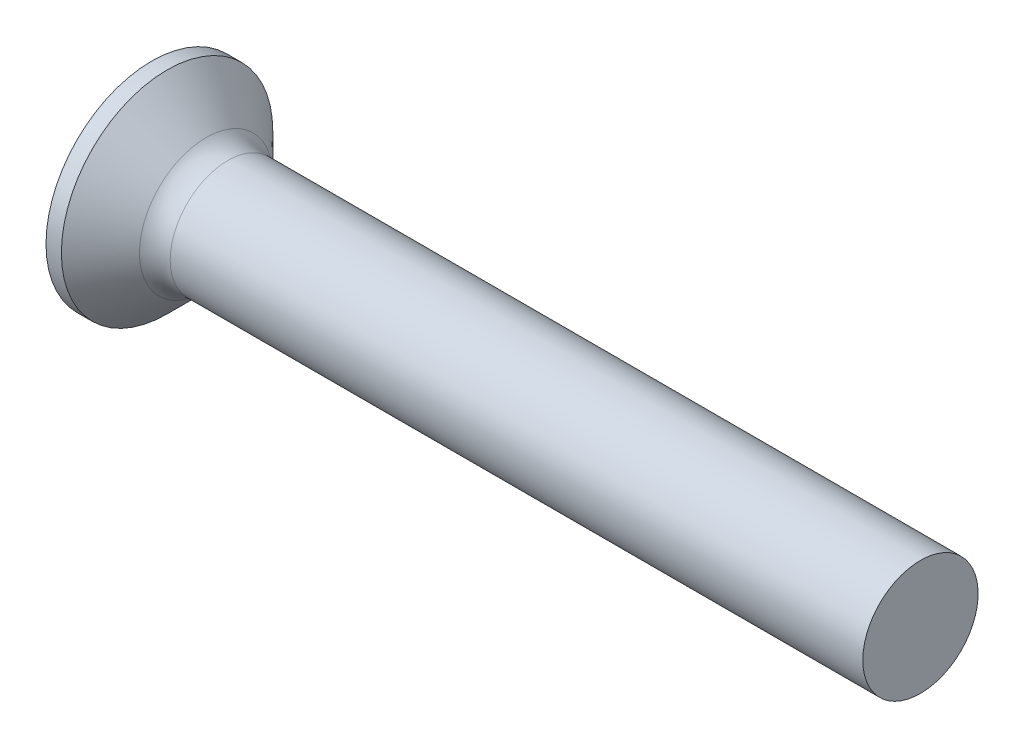
SolidWorks part; units mm, degrees
revolve "Base-Revolve" add sketch "BodySke"
sketch "BodySke" plane through (0, 0, 0) normal (0, 0, 1) x (1, 0, 0)
  line L0 (0, 0) -> (0, 2.75)
  line L1 (0, 2.75) -> (0.4, 2.75)
  line L2 (1.65, 1.5) -> (20, 1.5)
  line L3 (20, 1.5) -> (20, 0)
  line L4 (20, 0) -> (0, 0)
  line L5 (-6.35, 0) -> (82.55, 0) construction
  line L6 (1.65, -1.5) -> (20, -1.5) construction
  line L7 (0.4, -2.75) -> (1.65, -1.5) construction
  line L8 (0.4, 2.75) -> (1.65, 1.5)
  line L9 (0, -2.75) -> (0.4, -2.75) construction
  line L10 (2.15, 3.0875) -> (2.15, -6.4375) construction
  line L11 (0, 6.35) -> (0, -3.175) construction
  dimension "Diameter" = 3
  dimension "Length" = 20
  dimension "Head_ht" = 1.65
  dimension "Head_dia" = 5.5
  dimension "Head_ang" = 90
  dimension "D6" = 0.4
  dimension "Advance" = 0.5
  dimension "Thread_nom" = 20
cosmetic thread "ThreadCosmetic"
fillet "Fillet1" radius 0.8 1 edges at (1.65, 0, 1.5)
ref_plane "Plane1" through (0, 0, 0) normal (0, 0, 1) x (1, 0, 0)
ref_plane "Plane2" through (0, 0, 0) normal (0, 1, 0) x (1, 0, 0)
ref_plane "Plane3" through (0, 0, 0) normal (1, 0, 0) x (0, 0, -1)
sketch "Sketch3" plane through (0, 0, 0) normal (-1, 0, 0) x (0, 0, 1)
  line L0 (-0.37, 1.5) -> (0.37, 1.5)
  line L1 (0.37, 1.5) -> (0.37, -1.5)
  line L2 (0.37, -1.5) -> (-0.37, -1.5)
  line L3 (-0.37, -1.5) -> (-0.37, 1.5)
  dimension "Cross_dia" = 3
  dimension "Cross_width" = 0.74
  dimension "D1" = 1.5
  dimension "D2" = 0.37
ref_plane "Plane4" through (2.01, 0, 0) normal (-1, 0, 0) x (0, 0, 1)
sketch "Sketch4" plane through (2.01, 0, 0) normal (-1, 0, 0) x (0, 0, 1)
  line L0 (-0.37, 0.4979) -> (0.37, 0.4979)
  line L3 (0.37, 0.4979) -> (0.37, -0.4979)
  line L4 (0.37, -0.4979) -> (-0.37, -0.4979)
  line L5 (-0.37, -0.4979) -> (-0.37, 0.4979)
  dimension "D2" = 0.9957
  dimension "D1" = 0.74
  dimension "D4" = 0.4979
  dimension "D3" = 0.37
loft "Recess" cut profiles "Sketch3", "Sketch4"
pattern_circular "RecPat" count 2 every 90 about axis through (0, 0, 0) along (1, 0, 0) of "Recess"
sketch "RecCorSke" plane through (0, 0, 0) normal (0, 0, 1) x (1, 0, 0)
  line L0 (-3.175, 0) -> (15.875, 0) construction
  line L2 (0, 0) -> (0, 0.6966)
  line L3 (0, 0.6966) -> (2.01, 0.556)
  line L4 (2.01, 0.556) -> (2.1907, 0)
  line L5 (2.1907, 0) -> (0, 0)
  dimension "Diameter" = 1.112
  dimension "Depth" = 2.01
  dimension "Draft_angle" = 4
  dimension "Bottom_angle" = 18
revolve "RecessCore" cut sketch "RecCorSke" angle 360 about L0
sketch "ThdSchSke" plane through (0, 0, 0) normal (0, 0, 1) x (1, 0, 0)
  line L0 (2.15, -1.2195) -> (1.9536, -1.5)
  line L1 (2.15, -1.2195) -> (2.3464, -1.5)
  line L2 (2.3464, -1.5) -> (2.3464, -1.875)
  line L3 (-3.175, 0) -> (5.1513, 0) construction
  line L5 (2.3464, -1.875) -> (1.9536, -1.875)
  line L6 (1.9536, -1.875) -> (1.9536, -1.5)
  line L7 (0, 2.75) -> (0, -2.75) construction
  dimension "Diameter" = 3
  dimension "Thread_minor" = 2.439
  dimension "Start" = 2.15
revolve "ThreadSchematic" [suppressed] cut sketch "ThdSchSke" angle 360 about L3
pattern_linear "ThdSchPat" [suppressed]
equation "\"D1@Sketch3\" = \"Cross_dia@Sketch3\" / 2"
equation "\"D2@Sketch3\" = \"Cross_width@Sketch3\" / 2"
equation "\"Depth@RecCorSke\" = \"Cross_depth@Plane4\""
equation "\"D1@Sketch4\" = \"Cross_width@Sketch3\""
equation "\"D2@Sketch4\" = \"Cross_dia@Sketch3\" - 2.0 * \"Cross_depth@Plane4\" * tan(26.5  * 0.017453292)"
equation "\"D3@Sketch4\" = \"D1@Sketch4\" / 2"
equation "\"D4@Sketch4\" = \"D2@Sketch4\" / 2"
equation "\"Thread_length@ThreadCosmetic\" = ((sgn( (\"Length@BodySke\" - \"Advance@BodySke\" * 1.0 - \"Head_ht@BodySke\" ) - \"Thread_nom@BodySke\" )-1)*( (\"Length@BodySke\" - \"Advance@BodySke\" * 1.0 - \"Head_ht@BodySke\" ) - \"Thread_nom@BodySke\" ))/-2+ \"Thread_nom@BodySke\""
equation "\"Thread_minor@ThdSchSke\" = \"Thread_minor@ThreadCosmetic\""
equation "\"Diameter@ThdSchSke\" = \"Diameter@BodySke\""
equation "\"Overcut@ThdSchSke\" = \"Diameter@BodySke\" * 1.25"
equation "\"Start@ThdSchSke\" = 0.000001 + \"Length@BodySke\" - \"Thread_length@ThreadCosmetic\"  '---Countersunk---"
equation "\"Num_threads@ThdSchPat\" = int( \"Thread_length@ThreadCosmetic\" / \"Advance@BodySke\" + 0.999 )  + 1"
equation "\"Advance@ThdSchPat\" = \"Thread_length@ThreadCosmetic\" /  (\"Num_threads@ThdSchPat\" - 1) 'relax it"
